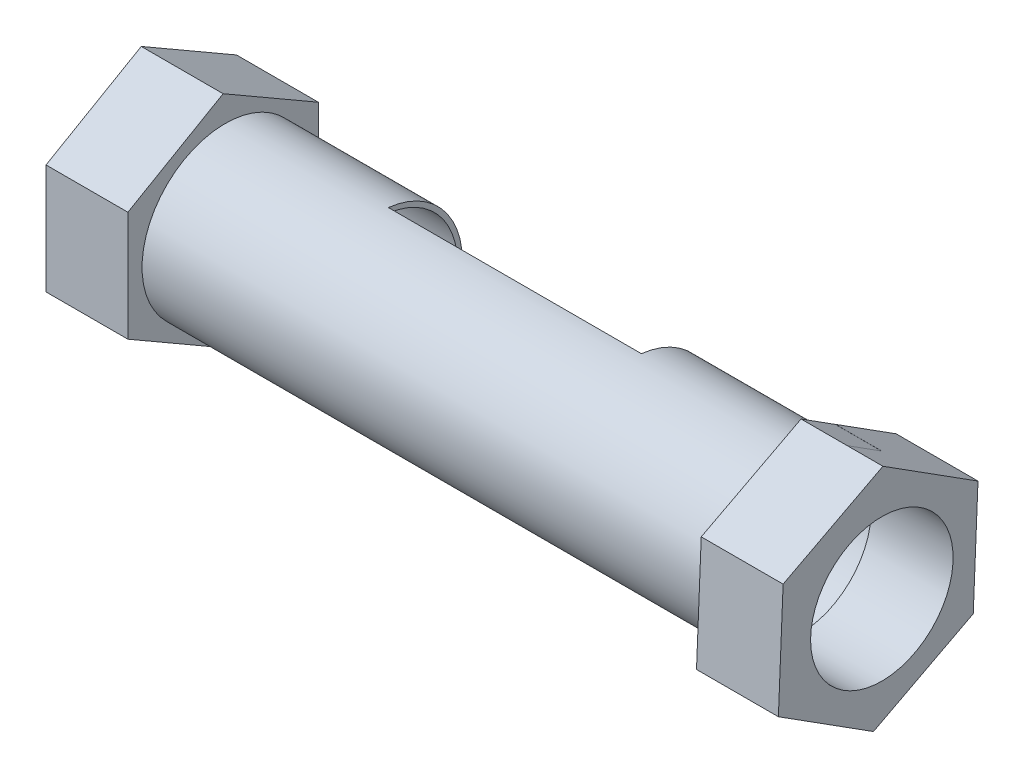
SolidWorks part; units mm, degrees
ref_plane "Front Plane" through (0, 0, 0) normal (0, 0, 1) x (1, 0, 0)
ref_plane "Top Plane" through (0, 0, 0) normal (0, 1, 0) x (1, 0, 0)
ref_plane "Right Plane" through (0, 0, 0) normal (1, 0, 0) x (0, 0, -1)
sketch "Sketch1" plane through (0, 0, 0) normal (1, 0, 0) x (0, 0, -1)
  circle A0 centre (1.2897, 0) radius 50.8004
  circle A1 centre (1.2897, 0) radius 47.813
extrude "Boss-Extrude2" add sketch "Sketch1" along normal blind 350
sketch "Sketch3" plane through (350, 0, 0) normal (1, 0, 0) x (0, 0, -1)
  line L1 (29.4119, -18.9904) -> (30.3159, 11.3837)
  line L2 (30.3159, 11.3837) -> (4.4631, 27.3538)
  line L3 (4.4631, 27.3538) -> (-22.2937, 12.9496)
  line L4 (-22.2937, 12.9496) -> (-23.1978, -17.4246)
  line L5 (-23.1978, -17.4246) -> (2.655, -33.3946)
  line L6 (2.655, -33.3946) -> (29.4119, -18.9904)
  line L7 (58.0556, -36.8554) -> (60.9455, 31.8499)
  line L8 (60.9455, 31.8499) -> (2.8899, 68.7054)
  line L9 (2.8899, 68.7054) -> (-58.0556, 36.8554)
  line L10 (-58.0556, 36.8554) -> (-60.9455, -31.8499)
  line L11 (-60.9455, -31.8499) -> (-2.8899, -68.7054)
  line L12 (-2.8899, -68.7054) -> (58.0556, -36.8554)
  circle A0 centre (3.5591, -3.0204) radius 26.3165 construction
  circle A1 centre (0, 0) radius 59.5532 construction
extrude "Boss-Extrude5" add sketch "Sketch3" along normal blind 50
sketch "Sketch5" plane through (0, 0, 0) normal (-1, 0, 0) x (0, 0, 1)
  line L1 (0, -67.1614) -> (58.1634, -33.5807)
  line L2 (58.1634, -33.5807) -> (58.1634, 33.5807)
  line L3 (58.1634, 33.5807) -> (0, 67.1614)
  line L4 (0, 67.1614) -> (-58.1634, 33.5807)
  line L5 (-58.1634, 33.5807) -> (-58.1634, -33.5807)
  line L6 (-58.1634, -33.5807) -> (0, -67.1614)
  circle A0 centre (0, 0) radius 58.1634 construction
extrude "Boss-Extrude11" add sketch "Sketch5" along normal blind 50
sketch "Sketch6" plane through (0, 0, 0) normal (1, 0, 0) x (0, 0, -1)
  circle A0 centre (2.1673, 0) radius 44.9963
extrude "Cut-Extrude2" cut sketch "Sketch6" against normal blind 50
sketch "Sketch7" plane through (350, 0, 0) normal (-1, 0, 0) x (0, 0, 1)
  circle A0 centre (-2.2315, -1.0944) radius 43.5179
extrude "Cut-Extrude3" cut sketch "Sketch7" against normal blind 50
sketch "Sketch10" plane through (0, 50.2776, -31.9177) normal (0, 0.8442, -0.536) x (1, 0, 0)
  line L1 (378.2622, -9.5899) -> (359.1464, -9.5899)
  line L2 (378.2622, -9.5899) -> (378.2622, -30.3322)
  line L3 (378.2622, -30.3322) -> (359.1464, -30.3322)
  line L4 (359.1464, -9.5899) -> (359.1464, -30.3322)
extrude "Boss-Extrude12" add sketch "Sketch10" along normal blind 50
sketch "Sketch11" plane through (378.2622, 0, 0) normal (1, 0, 0) x (0, 0, -1)
  line L1 (8.5874, 114.1852) -> (62.9523, 114.1852)
  line L2 (8.5874, 114.1852) -> (8.5874, 87.8152)
  line L3 (8.5874, 87.8152) -> (62.9523, 87.8152)
  line L4 (62.9523, 114.1852) -> (62.9523, 87.8152)
extrude "Cut-Extrude6" cut sketch "Sketch11" against normal blind 50
sketch "Sketch12" plane through (0, 87.8152, 0) normal (0, 1, 0) x (1, 0, 0)
  line L1 (248.5224, 6.9131) -> (93.9668, 6.9131)
  line L2 (248.5224, 6.9131) -> (248.5224, 196.5999)
  line L3 (248.5224, 196.5999) -> (93.9668, 196.5999)
  line L4 (93.9668, 6.9131) -> (93.9668, 196.5999)
extrude "Cut-Extrude7" cut sketch "Sketch12" against normal through all
sketch "Sketch13" plane through (378.2622, 0, 0) normal (1, 0, 0) x (0, 0, -1)
  line L1 (2.7674, 94.3538) -> (53.1269, 94.3538)
  line L2 (2.7674, 94.3538) -> (1.7844, 69.4068)
  line L3 (1.7844, 69.4068) -> (23.9047, 55.316)
  line L4 (53.1269, 94.3538) -> (23.9047, 55.316)
extrude "Cut-Extrude9" cut sketch "Sketch13" against normal blind 50
